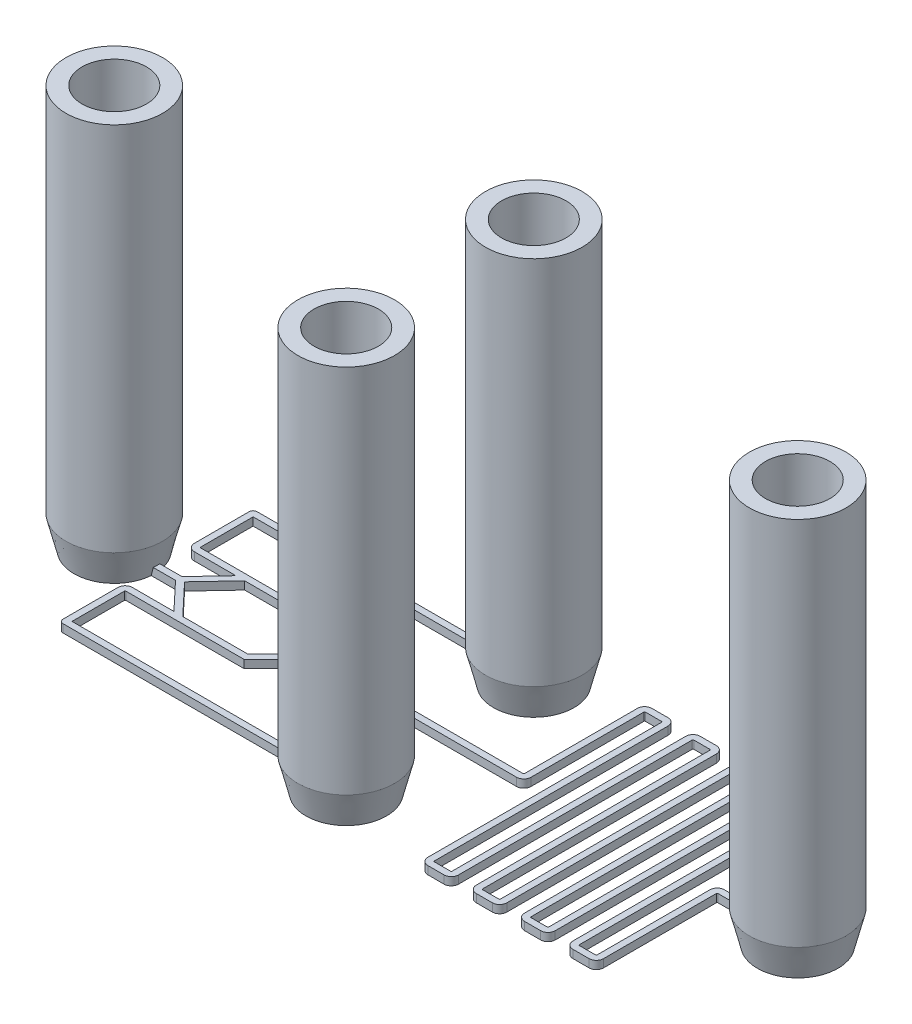
SolidWorks part; units mm, degrees
ref_plane "Front Plane" through (0, 0, 0) normal (0, 0, 1) x (1, 0, 0)
ref_plane "Top Plane" through (0, 0, 0) normal (0, 1, 0) x (1, 0, 0)
ref_plane "Right Plane" through (0, 0, 0) normal (1, 0, 0) x (0, 0, -1)
sketch "skelton" plane through (0, 0, 0) normal (0, 0, 1) x (1, 0, 0)
  line L0 (-100, 0) -> (100, 0) construction
  point P4 (0, 0)
sketch "Sketch2" plane through (0, 0, 0) normal (0, 1, 0) x (1, 0, 0)
  line L7 (-100, 0) -> (100, 0) construction
  line L13 (-31.8426, 11.2426) -> (2.6, 11.2426)
  line L15 (-31.8426, -12.0426) -> (2.6, -12.0426)
  line L16 (6.7, 0.4) -> (-12.8343, 0.4)
  line L17 (-31.8426, 12.0426) -> (2.6, 12.0426)
  line L18 (-31.8426, -11.2426) -> (2.6, -11.2426)
  line L19 (-31.8426, 12.0426) -> (-32.1426, 12.0426)
  line L20 (-31.8426, -12.0426) -> (-32.1426, -12.0426)
  line L39 (-12.8343, 0.4) -> (-17.077, 4.6426)
  line L40 (-26.036, 3.8426) -> (-29.6589, 0) construction
  line L41 (-29.6589, 0) -> (-26.036, -3.8426) construction
  line L43 (-17.077, 4.6426) -> (-31.7426, 4.6426)
  line L44 (-31.8426, 4.7426) -> (-31.8426, 11.2426)
  line L45 (-13.5657, 0) -> (-17.4083, -3.8426)
  line L46 (-17.4083, -3.8426) -> (-25.4863, -3.8426)
  line L47 (-32.6426, -4.7426) -> (-32.6426, -11.5426)
  line L48 (-26.5858, 3.8426) -> (-31.7426, 3.8426)
  line L49 (-29.8315, -0.4) -> (-26.5858, -3.8426)
  line L50 (-29.8315, 0.4) -> (-37.8315, 0.4)
  line L51 (6.7, -0.4) -> (12.5, -0.4)
  line L52 (13.4, 14.5) -> (13.4, 0.5)
  line L53 (13.5, 14.6) -> (15.5, 14.6)
  line L54 (15.6, 14.5) -> (15.6, 0)
  line L55 (15.6, 0) -> (15.6, -14.5)
  line L56 (16.5, -15.4) -> (18.5, -15.4)
  line L57 (19.4, -14.5) -> (19.4, 14.5)
  line L58 (19.5, 14.6) -> (21.5, 14.6)
  line L59 (21.6, 14.5) -> (21.6, -14.5)
  line L60 (22.5, -15.4) -> (24.5, -15.4)
  line L61 (25.4, -14.5) -> (25.4, 14.5)
  line L62 (25.5, 14.6) -> (27.5, 14.6)
  line L63 (27.6, 14.5) -> (27.6, -14.5)
  line L64 (28.5, -15.4) -> (30.5, -15.4)
  line L65 (31.4, -14.5) -> (31.4, 14.5)
  line L66 (31.5, 14.6) -> (33.5, 14.6)
  line L67 (33.6, 14.5) -> (33.6, -14.5)
  line L68 (34.5, -15.4) -> (36.5, -15.4)
  line L69 (37.4, -14.5) -> (37.4, -0.5)
  line L70 (37.5, -0.4) -> (47, -0.4)
  line L71 (6.7, -0.4) -> (-12.8343, -0.4)
  line L72 (-13.5657, 0) -> (-17.4083, 3.8426)
  line L73 (-17.4083, 3.8426) -> (-25.4863, 3.8426)
  line L74 (-32.6426, 4.7426) -> (-32.6426, 11.5426)
  line L75 (-12.8343, -0.4) -> (-17.077, -4.6426)
  line L76 (-17.077, -4.6426) -> (-31.7426, -4.6426)
  line L77 (-31.8426, -4.7426) -> (-31.8426, -11.2426)
  line L78 (-25.4863, 3.8426) -> (-29.1091, 0)
  line L79 (-29.1091, 0) -> (-25.4863, -3.8426)
  line L80 (-29.8315, -0.4) -> (-37.8315, -0.4)
  line L81 (6.7, 0.4) -> (12.5, 0.4)
  line L82 (12.6, 14.5) -> (12.6, 0.5)
  line L83 (13.5, 15.4) -> (15.5, 15.4)
  line L84 (16.4, 14.5) -> (16.4, 0)
  line L85 (16.4, 0) -> (16.4, -14.5)
  line L86 (16.5, -14.6) -> (18.5, -14.6)
  line L87 (18.6, -14.5) -> (18.6, 14.5)
  line L88 (19.5, 15.4) -> (21.5, 15.4)
  line L89 (22.4, 14.5) -> (22.4, -14.5)
  line L90 (22.5, -14.6) -> (24.5, -14.6)
  line L91 (24.6, -14.5) -> (24.6, 14.5)
  line L92 (25.5, 15.4) -> (27.5, 15.4)
  line L93 (28.4, 14.5) -> (28.4, -14.5)
  line L94 (28.5, -14.6) -> (30.5, -14.6)
  line L95 (30.6, -14.5) -> (30.6, 14.5)
  line L96 (31.5, 15.4) -> (33.5, 15.4)
  line L97 (34.4, 14.5) -> (34.4, -14.5)
  line L98 (34.5, -14.6) -> (36.5, -14.6)
  line L99 (36.6, -14.5) -> (36.6, -0.5)
  line L100 (37.5, 0.4) -> (47, 0.4)
  line L101 (-26.5858, 3.8426) -> (-29.8315, 0.4)
  line L103 (-25.6589, 4.2426) -> (-29.6589, 0) construction
  line L105 (-25.3678, 3.9682) -> (-29.3678, -0.2744) construction
  line L106 (-29.3678, 0.2744) -> (-25.3678, -3.9682) construction
  line L109 (-29.9499, -0.2744) -> (-25.9499, -4.517) construction
  line L110 (-29.6589, 0) -> (-25.6589, -4.2426) construction
  line L111 (-26.5858, -3.8426) -> (-31.7426, -3.8426)
  arc A5 (2.6, 11.2426) -> (2.6, 12.0426) centre (2.6, 11.6426) ccw
  arc A6 (2.6, -12.0426) -> (2.6, -11.2426) centre (2.6, -11.6426) ccw
  arc A7 (-37.8315, 0.4) -> (-37.8315, -0.4) centre (-37.8315, 0) ccw
  arc A8 (-32.1426, -12.0426) -> (-32.6426, -11.5426) centre (-32.1426, -11.5426) cw
  arc A9 (-32.6426, 11.5426) -> (-32.1426, 12.0426) centre (-32.1426, 11.5426) cw
  arc A20 (-31.7426, 4.6426) -> (-31.8426, 4.7426) centre (-31.7426, 4.7426) cw
  arc A21 (-31.7426, -3.8426) -> (-32.6426, -4.7426) centre (-31.7426, -4.7426) ccw
  arc A22 (12.5, -0.4) -> (13.4, 0.5) centre (12.5, 0.5) ccw
  arc A23 (13.4, 14.5) -> (13.5, 14.6) centre (13.5, 14.5) cw
  arc A24 (15.5, 14.6) -> (15.6, 14.5) centre (15.5, 14.5) cw
  arc A25 (15.6, -14.5) -> (16.5, -15.4) centre (16.5, -14.5) ccw
  arc A26 (18.5, -15.4) -> (19.4, -14.5) centre (18.5, -14.5) ccw
  arc A27 (19.4, 14.5) -> (19.5, 14.6) centre (19.5, 14.5) cw
  arc A28 (21.5, 14.6) -> (21.6, 14.5) centre (21.5, 14.5) cw
  arc A29 (21.6, -14.5) -> (22.5, -15.4) centre (22.5, -14.5) ccw
  arc A30 (24.5, -15.4) -> (25.4, -14.5) centre (24.5, -14.5) ccw
  arc A31 (25.4, 14.5) -> (25.5, 14.6) centre (25.5, 14.5) cw
  arc A32 (27.5, 14.6) -> (27.6, 14.5) centre (27.5, 14.5) cw
  arc A33 (27.6, -14.5) -> (28.5, -15.4) centre (28.5, -14.5) ccw
  arc A34 (30.5, -15.4) -> (31.4, -14.5) centre (30.5, -14.5) ccw
  arc A35 (31.4, 14.5) -> (31.5, 14.6) centre (31.5, 14.5) cw
  arc A36 (33.5, 14.6) -> (33.6, 14.5) centre (33.5, 14.5) cw
  arc A37 (33.6, -14.5) -> (34.5, -15.4) centre (34.5, -14.5) ccw
  arc A38 (36.5, -15.4) -> (37.4, -14.5) centre (36.5, -14.5) ccw
  arc A39 (37.4, -0.5) -> (37.5, -0.4) centre (37.5, -0.5) cw
  arc A40 (-31.7426, 3.8426) -> (-32.6426, 4.7426) centre (-31.7426, 4.7426) cw
  arc A41 (-31.7426, -4.6426) -> (-31.8426, -4.7426) centre (-31.7426, -4.7426) ccw
  arc A42 (12.5, 0.4) -> (12.6, 0.5) centre (12.5, 0.5) ccw
  arc A43 (12.6, 14.5) -> (13.5, 15.4) centre (13.5, 14.5) cw
  arc A44 (15.5, 15.4) -> (16.4, 14.5) centre (15.5, 14.5) cw
  arc A45 (16.4, -14.5) -> (16.5, -14.6) centre (16.5, -14.5) ccw
  arc A46 (18.5, -14.6) -> (18.6, -14.5) centre (18.5, -14.5) ccw
  arc A47 (18.6, 14.5) -> (19.5, 15.4) centre (19.5, 14.5) cw
  arc A48 (21.5, 15.4) -> (22.4, 14.5) centre (21.5, 14.5) cw
  arc A49 (22.4, -14.5) -> (22.5, -14.6) centre (22.5, -14.5) ccw
  arc A50 (24.5, -14.6) -> (24.6, -14.5) centre (24.5, -14.5) ccw
  arc A51 (24.6, 14.5) -> (25.5, 15.4) centre (25.5, 14.5) cw
  arc A52 (27.5, 15.4) -> (28.4, 14.5) centre (27.5, 14.5) cw
  arc A53 (28.4, -14.5) -> (28.5, -14.6) centre (28.5, -14.5) ccw
  arc A54 (30.5, -14.6) -> (30.6, -14.5) centre (30.5, -14.5) ccw
  arc A55 (30.6, 14.5) -> (31.5, 15.4) centre (31.5, 14.5) cw
  arc A56 (33.5, 15.4) -> (34.4, 14.5) centre (33.5, 14.5) cw
  arc A57 (34.4, -14.5) -> (34.5, -14.6) centre (34.5, -14.5) ccw
  arc A58 (36.5, -14.6) -> (36.6, -14.5) centre (36.5, -14.5) ccw
  arc A59 (36.6, -0.5) -> (37.5, 0.4) centre (37.5, -0.5) cw
  arc A67 (47, -0.4) -> (47, 0.4) centre (47, 0) ccw
  point P0 (0, 0)
  point P19 (-25.6589, 0)
  point P24 (13, 0)
  point P43 (37, -15)
  point P46 (34, -15)
  point P49 (31, -15)
  point P52 (28, -15)
  point P55 (25, -15)
  point P58 (22, -15)
  point P61 (19, -15)
  point P64 (16, -15)
  point P67 (13, 0)
  point P70 (-32.2426, -4.2426)
  point P73 (-32.2426, 4.2426)
  point P76 (37, 0)
  point P79 (34, 15)
  point P82 (31, 15)
  point P85 (28, 15)
  point P88 (25, 15)
  point P91 (22, 15)
  point P94 (19, 15)
  point P97 (16, 15)
  point P100 (13, 15)
  dimension "D11" = 0.5
  dimension "D14" = 0.5
  dimension "D1" = 3
  dimension "D2" = 3
  dimension "D4" = 3
  dimension "D5" = 3
  dimension "D6" = 3
  dimension "D7" = 3
  dimension "D8" = 3
  dimension "D9" = 3
  dimension "D18" = 30
  dimension "D20" = 0.4
  dimension "D21" = 0.4
extrude "skelton_extru" add sketch "Sketch2" along normal blind 1
ref_plane "Plane1" through (0, 0, -11.6426) normal (0, 0, 1) x (1, 0, 0)
sketch "Sketch3" plane through (0, 0, -11.6426) normal (0, 0, 1) x (1, 0, 0)
  line L0 (2.6, 0) -> (7.6, 0)
  line L1 (-100, 0) -> (100, 0) construction
  line L3 (2.6, 0) -> (2.6, 50)
  line L4 (2.6, 50) -> (8.6, 50)
  line L5 (8.6, 50) -> (8.6, 4)
  line L6 (8.6, 4) -> (7.6, 0)
  dimension "D1" = 5
  dimension "D3" = 50
  dimension "D4" = 6
revolve "Revolve1" add sketch "Sketch3" angle 360 about L3
ref_plane "Plane2" through (0, 0, 0) normal (0, 0, -1) x (-1, 0, 0)
sketch "Sketch4" plane through (0, 0, 0) normal (0, 0, -1) x (-1, 0, 0)
  line L0 (-47, 0) -> (-52, 0)
  line L1 (100, 0) -> (-100, 0) construction
  line L3 (-47, 0) -> (-47, 50)
  line L4 (-47, 50) -> (-53, 50)
  line L5 (-53, 50) -> (-53, 4)
  line L6 (-53, 4) -> (-52, 0)
  dimension "D1" = 5
  dimension "D3" = 50
  dimension "D4" = 6
revolve "Revolve2" add sketch "Sketch4" angle 360 about L3
ref_plane "Plane3" through (0, 0, 0) normal (0, 0, -1) x (-1, 0, 0)
sketch "Sketch5" plane through (0, 0, 0) normal (0, 0, -1) x (-1, 0, 0)
  line L0 (37.8315, 50) -> (37.8315, 0)
  line L1 (37.8315, 0) -> (42.8315, 0)
  line L2 (100, 0) -> (-100, 0) construction
  line L4 (37.8315, 50) -> (43.8315, 50)
  line L5 (43.8315, 50) -> (43.8315, 4)
  line L6 (43.8315, 4) -> (42.8315, 0)
  dimension "D1" = 50
  dimension "D2" = 5
  dimension "D4" = 6
revolve "Revolve3" add sketch "Sketch5" angle 360 about L0
ref_plane "Plane4" through (0, 0, 11.6426) normal (0, 0, 1) x (1, 0, 0)
sketch "Sketch6" plane through (0, 0, 11.6426) normal (0, 0, 1) x (1, 0, 0)
  line L0 (2.6, 0) -> (7.6, 0)
  line L1 (-100, 0) -> (100, 0) construction
  line L3 (2.6, 0) -> (2.6, 50)
  line L4 (2.6, 50) -> (8.6, 50)
  line L5 (8.6, 50) -> (8.6, 4)
  line L6 (8.6, 4) -> (7.6, 0)
  dimension "D1" = 5
  dimension "D3" = 50
  dimension "D4" = 6
revolve "Revolve4" add sketch "Sketch6" angle 360 about L3
sketch "Sketch8" plane through (0, 50, 0) normal (0, 1, 0) x (1, 0, 0)
  circle A0 centre (-37.8315, 0) radius 4
  circle A1 centre (2.6, 11.6426) radius 4
  circle A2 centre (2.6, -11.6426) radius 4
  circle A3 centre (47, 0) radius 4
  dimension "D1" = 8
  dimension "D2" = 8
  dimension "D3" = 8
  dimension "D4" = 8
extrude "Cut-Extrude1" cut sketch "Sketch8" against normal blind 45
